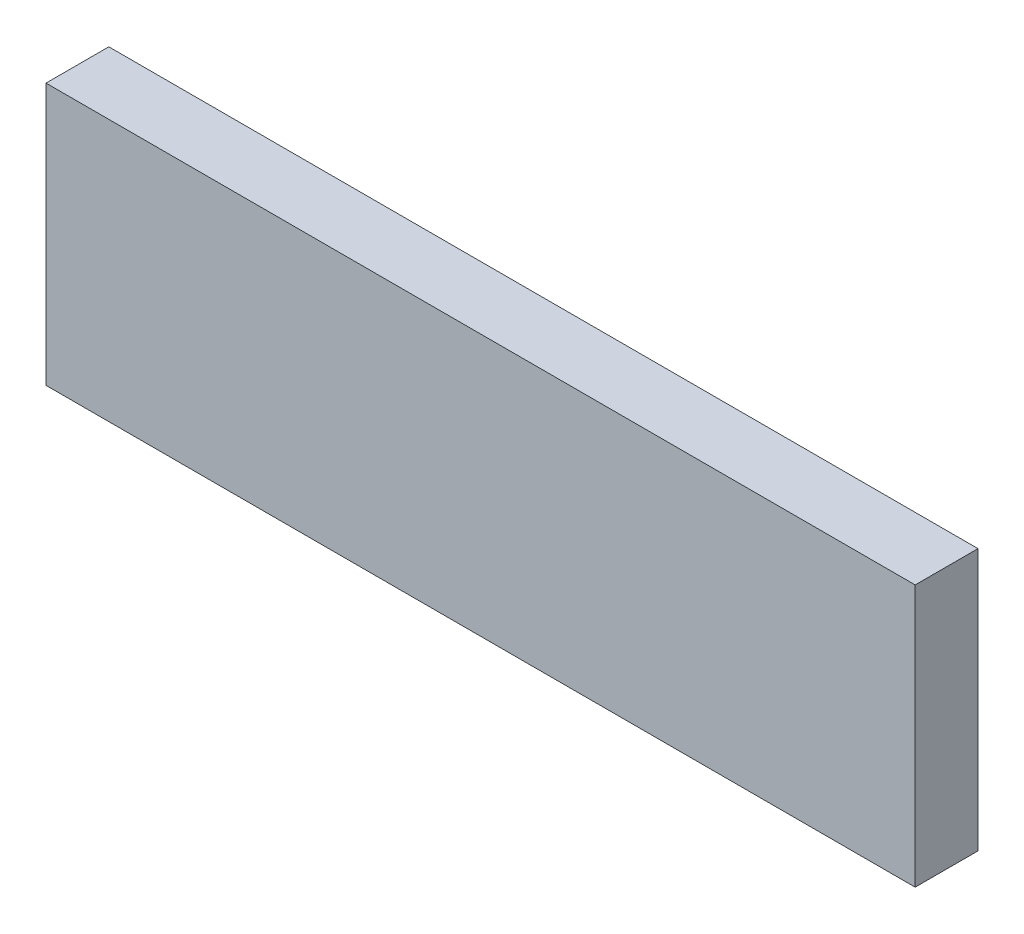
SolidWorks part; units mm, degrees
material "Pine"
ref_plane "Front Plane" through (0, 0, 0) normal (0, 0, 1) x (1, 0, 0)
ref_plane "Top Plane" through (0, 0, 0) normal (0, 1, 0) x (1, 0, 0)
ref_plane "Right Plane" through (0, 0, 0) normal (1, 0, 0) x (0, 0, -1)
sketch "Sketch3" plane through (0, 0, 0) normal (0, 0, 1) x (1, 0, 0)
  line L4 (417, 50) -> (583, 50)
  line L5 (417, 50) -> (417, 0)
  line L6 (417, 0) -> (583, 0)
  line L7 (583, 50) -> (583, 0)
  line L8 (417, 50) -> (583, 0) construction
  line L9 (417, 0) -> (583, 50) construction
  point P6 (500, 25)
  dimension "D1" = 166
  dimension "D2" = 50
extrude "Boss-Extrude2" add sketch "Sketch3" along normal blind 12 separate body
equation "\"LENGTH\" = 1000mm"
equation "\"PLY\"= 12mm"
equation "\"CENTER_BRACE_LENGTH\" = 393mm"
equation "\"PANEL_WIDTH\"= \"LENGTH\" - \"CENTER_BRACE_LENGTH\" * 2 - \"PLY\" * 4"
equation "\"D1@Boss-Extrude2\"=\"PLY\""
equation "\"D1@Sketch3\"=\"PANEL_WIDTH\""
equation "\"PANEL_SMALL_HEIGHT\" = 70mm"
equation "\"WIDTH\" = 300mm"
